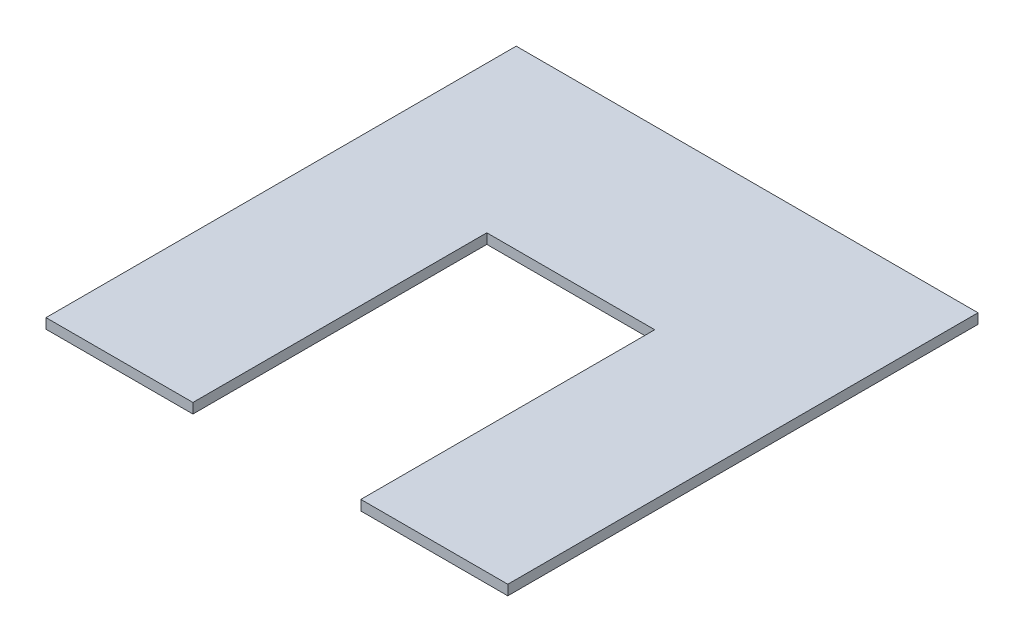
SolidWorks part; units mm, degrees
ref_plane "Front Plane" through (0, 0, 0) normal (0, 0, 1) x (1, 0, 0)
ref_plane "Top Plane" through (0, 0, 0) normal (0, 1, 0) x (1, 0, 0)
ref_plane "Right Plane" through (0, 0, 0) normal (1, 0, 0) x (0, 0, -1)
sketch "Sketch1" plane through (0, 0, 0) normal (0, 1, 0) x (1, 0, 0)
  line L0 (-105.8695, 41.3977) -> (169.1305, 41.3977)
  line L1 (-105.8695, 41.3977) -> (-105.8695, -238.6023)
  line L2 (169.1305, 41.3977) -> (169.1305, -238.6023)
  line L3 (-105.8695, -238.6023) -> (-18.3695, -238.6023)
  line L4 (169.1305, -238.6023) -> (81.6305, -238.6023)
  line L5 (-18.3695, -238.6023) -> (-18.3695, -63.6023)
  line L6 (81.6305, -238.6023) -> (81.6305, -63.6023)
  line L7 (-18.3695, -63.6023) -> (81.6305, -63.6023)
  point P5 (0, 0)
  dimension "D1" = 100
extrude "Boss-Extrude2" add sketch "Sketch1" along normal blind 6 contours L5 L7 L6 L4 L2 L0 L1 L3
